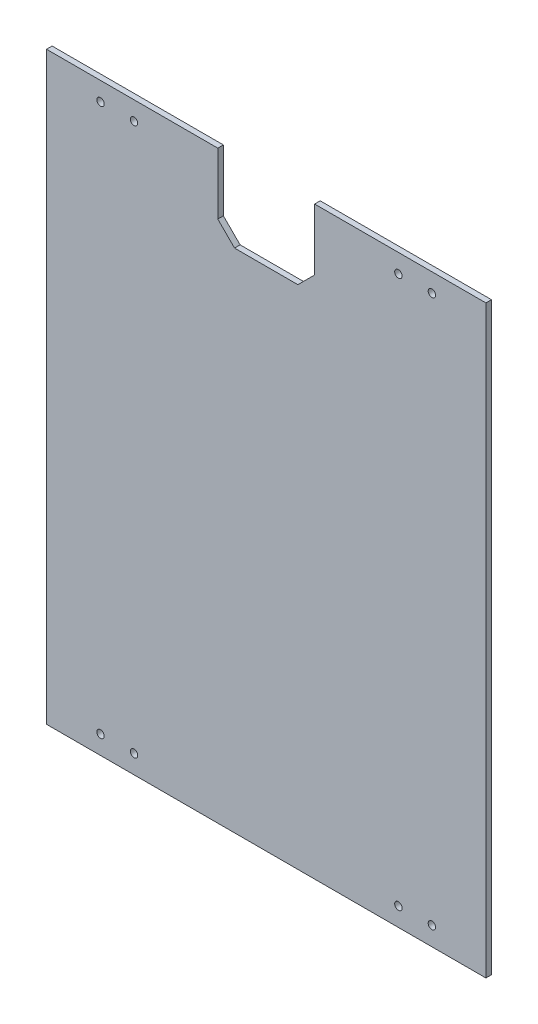
SolidWorks part; units mm, degrees
ref_plane "Plan de face" through (0, 0, 0) normal (0, 0, 1) x (1, 0, 0)
ref_plane "Plan de dessus" through (0, 0, 0) normal (0, 1, 0) x (1, 0, 0)
ref_plane "Plan de droite" through (0, 0, 0) normal (1, 0, 0) x (0, 0, -1)
sketch "Esquisse1" plane through (0, 0, 0) normal (0, 0, 1) x (1, 0, 0)
  line L0 (0, 0) -> (118, 0) construction
  line L1 (0, 0) -> (-118, 0) construction
  line L2 (-118, 0) -> (-118, 154) construction
  line L3 (-118, 154) -> (118, 154)
  line L4 (118, 154) -> (118, -160)
  line L5 (118, -160) -> (-118, -160)
  line L7 (-118, 154) -> (-118, -160)
  dimension "D1" = 160
  dimension "D2" = 118
  dimension "D4" = 314
extrude "Boss.-Extru.1" add sketch "Esquisse1" along normal blind 3
sketch "Esquisse3" plane through (0, 0, 3) normal (0, 0, 1) x (1, 0, 0)
  line L0 (0, -160) -> (-80, -160) construction
  line L1 (-118, -160) -> (118, -160) construction
  line L2 (-80, -160) -> (-80, -150) construction
  line L3 (-80, -150) -> (-71, -150) construction
  line L4 (-80, -150) -> (-89, -150) construction
  line L5 (-118, -3) -> (118, -3) construction
  line L6 (-118, 154) -> (-118, -160) construction
  line L7 (118, -160) -> (118, 154) construction
  line L8 (-80, 144) -> (-89, 144) construction
  line L9 (-80, 144) -> (-71, 144) construction
  line L10 (-80, 154) -> (-80, 144) construction
  line L11 (0, 154) -> (-80, 154) construction
  line L12 (0, -55) -> (0, 55) construction
  line L13 (80, 154) -> (80, 144) construction
  line L14 (80, 144) -> (71, 144) construction
  line L15 (80, 144) -> (89, 144) construction
  circle A0 centre (-71, -150) radius 2
  circle A1 centre (-89, -150) radius 2
  circle A2 centre (-89, 144) radius 2
  circle A3 centre (-71, 144) radius 2
  circle A4 centre (71, 144) radius 2
  circle A5 centre (89, 144) radius 2
  dimension "D3" = 9
  dimension "D1" = 10
  dimension "D2" = 9
extrude "Enlèv. mat.-Extru.1" cut sketch "Esquisse3" against normal up to next
mirror "Symétrie1" about plane through (0, 0, 0) normal (1, 0, 0) of "Enlèv. mat.-Extru.1"
sketch "Esquisse5" plane through (0, 0, 3) normal (0, 0, 1) x (1, 0, 0)
  line L0 (0, 154) -> (-118, 154) construction
  line L1 (118, 154) -> (-118, 154) construction
  line L2 (0, 154) -> (26, 154)
  line L3 (26, 154) -> (26, 121)
  line L4 (26, 121) -> (17, 121) construction
  line L5 (17, 121) -> (17, 112) construction
  line L6 (17, 112) -> (-17, 112)
  line L7 (-17, 112) -> (-17, 121) construction
  line L8 (-17, 121) -> (-26, 121) construction
  line L9 (-26, 121) -> (-26, 154)
  line L10 (-26, 154) -> (0, 154)
  line L11 (-26, 121) -> (-17, 112)
  line L12 (17, 112) -> (26, 121)
  point P12 (0, 152.8486)
  dimension "D1" = 26
  dimension "D2" = 33
  dimension "D3" = 9
  dimension "D4" = 9
  dimension "D5" = 34
  dimension "D6" = 9
  dimension "D7" = 9
  dimension "D8" = 33
extrude "Enlèv. mat.-Extru.2" cut sketch "Esquisse5" against normal up to next
